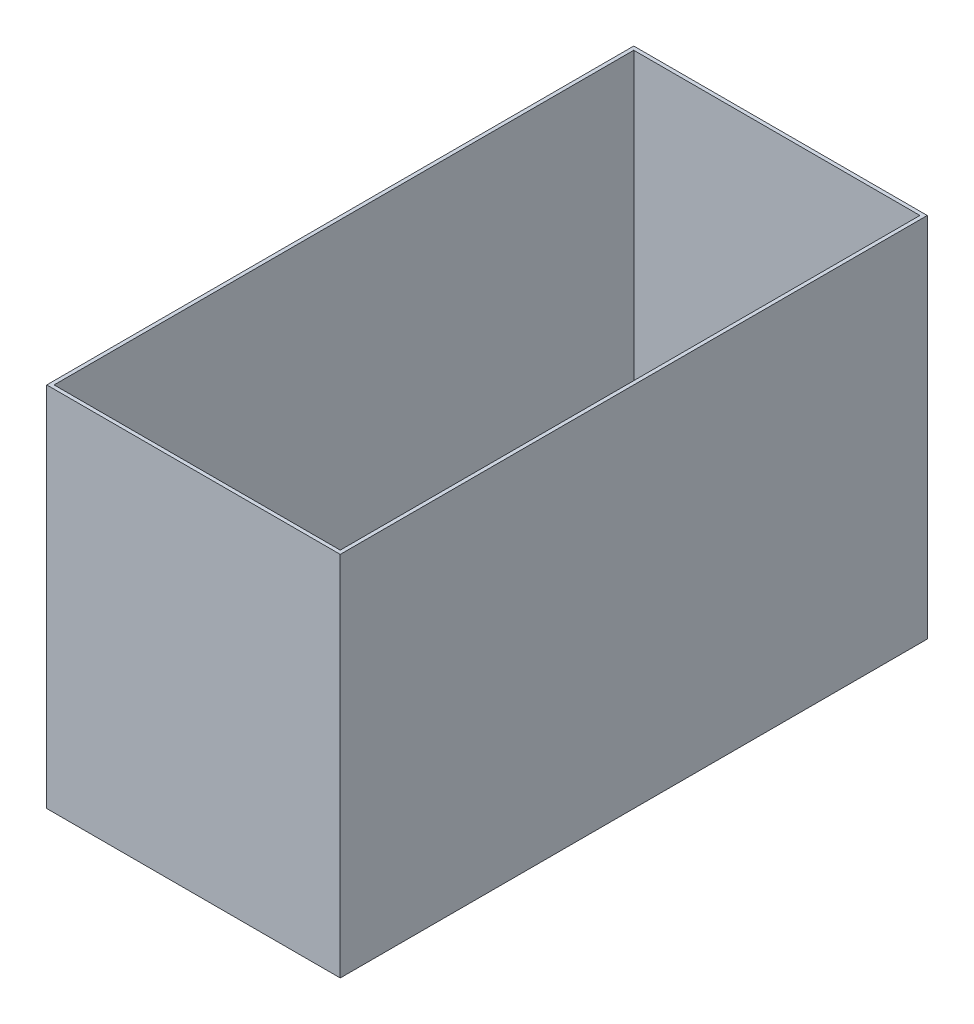
SolidWorks part; units mm, degrees
material "Glass"
ref_plane "Front Plane" through (0, 0, 0) normal (0, 0, 1) x (1, 0, 0)
ref_plane "Top Plane" through (0, 0, 0) normal (0, 1, 0) x (1, 0, 0)
ref_plane "Right Plane" through (0, 0, 0) normal (1, 0, 0) x (0, 0, -1)
sketch "Sketch1" plane through (0, 0, 0) normal (0, 1, 0) x (1, 0, 0)
  line L1 (-101.6, -203.2) -> (101.6, -203.2)
  line L2 (-101.6, -203.2) -> (-101.6, 203.2)
  line L3 (-101.6, 203.2) -> (101.6, 203.2)
  line L4 (101.6, -203.2) -> (101.6, 203.2)
  line L5 (-101.6, -203.2) -> (101.6, 203.2) construction
  line L6 (-101.6, 203.2) -> (101.6, -203.2) construction
  point P0 (0, 0)
  dimension "D1" = 203.2
  dimension "D2" = 406.4
extrude "Boss-Extrude1" add sketch "Sketch1" along normal blind 254
shell "Shell1" thickness 2.54
